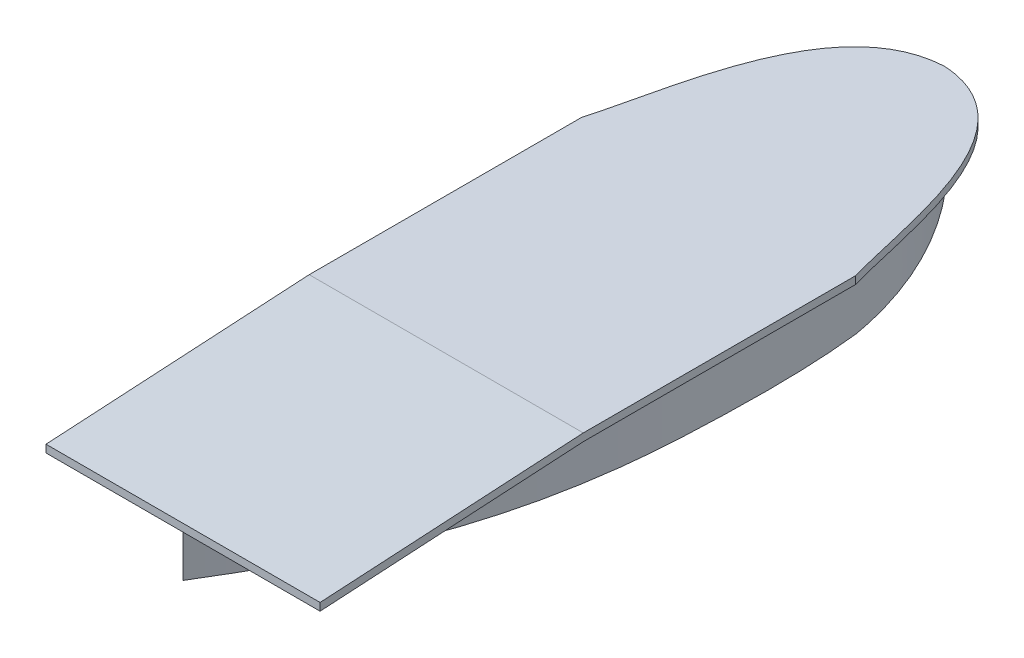
SolidWorks part; units mm, degrees
ref_plane "Front Plane" through (0, 0, 0) normal (0, 0, 1) x (1, 0, 0)
ref_plane "Top Plane" through (0, 0, 0) normal (0, 1, 0) x (1, 0, 0)
ref_plane "Right Plane" through (0, 0, 0) normal (1, 0, 0) x (0, 0, -1)
sketch "Sketch1" plane through (0, 0, 0) normal (0, 1, 0) x (1, 0, 0)
  line L0 (457.2, 5000) -> (457.2, 0) construction
  line L1 (0, 0) -> (914.4, 0) construction
  line L2 (0, 0) -> (0, 5000) construction
  line L3 (0, 5000) -> (914.4, 5000) construction
  line L4 (914.4, 0) -> (914.4, 5000) construction
  spline S0 degree 3 poles (457.2, 5000) (728.9155, 4811.3495) (923.1397, 4099.3682) (934.5582, 2393.6679) (728.4213, 982.7468) (457.2, 0) knots 0 0 0 0 0.183022 0.404936 1 1 1 1
  spline S1 degree 3 poles (457.2, 5000) (185.4845, 4811.3495) (-8.7397, 4099.3682) (-20.1582, 2393.6679) (185.9787, 982.7468) (457.2, 0) knots 0 0 0 0 0.183022 0.404936 1 1 1 1
  point P7 (180.2619, 4246.948)
  point P8 (228.0901, 3101.4628)
  point P9 (257.8987, 1620.2434)
  point P11 (0, 0)
  point P19 (104.7875, 4248.6526)
  point P20 (0, 3028.8666)
  point P21 (130.306, 1569.2064)
  point P22 (48.6467, 4172.097)
  point P23 (252.795, 4789.6455)
  dimension "D1" = 5000
  dimension "D2" = 914.4
extrude "Boss-Extrude1" add sketch "Sketch1" along normal blind 750 contours S0 S1
sketch "Sketch2" plane through (0, 0, 0) normal (1, 0, 0) x (0, 0, -1)
  line L10 (5000, 750) -> (0, 750) construction
  line L15 (1728.3497, 750) -> (0, 650)
  line L16 (0, 750) -> (0, 0) construction
  line L17 (1728.3497, 750) -> (3617.238, 750)
  line L18 (0, 0) -> (5000, 0) construction
  line L19 (0, 375) -> (1805.008, 0)
  line L20 (1805.008, 0) -> (3989.7721, 0)
  line L21 (0, 650) -> (0, 375)
  line L22 (5000, 750) -> (5000, 0) construction
  line L23 (-768.5235, 1443.0864) -> (6207.3897, 1443.0864)
  line L24 (-768.5235, 1443.0864) -> (-768.5235, -1130.4451)
  line L25 (-768.5235, -1130.4451) -> (6207.3897, -1130.4451)
  line L26 (6207.3897, 1443.0864) -> (6207.3897, -1130.4451)
  line L27 (3617.238, 750) -> (5000, 750)
  line L28 (5000, 750) -> (5000, 375)
  spline S1 degree 2 poles (5000, 375) (4563.55, 43.5842) (3989.7721, 0) knots 0 0 0 1 1 1
  dimension "D1" = 100
extrude "Cut-Extrude1" cut sketch "Sketch2" along normal blind 2867
sketch "Sketch3" plane through (0, 0, 0) normal (1, 0, 0) x (0, 0, -1)
  line L12 (3617.238, 800) -> (1728.3497, 800)
  line L13 (1728.3497, 800) -> (0, 700)
  line L14 (1728.3497, 750) -> (0, 650) construction
  line L15 (3617.238, 750) -> (1728.3497, 750) construction
  line L16 (1728.3497, 750) -> (0, 650)
  line L17 (3617.238, 750) -> (1728.3497, 750)
  line L18 (0, 700) -> (0, 650)
  line L20 (3617.238, 800) -> (5569.1616, 800)
  line L21 (5569.1616, 800) -> (5569.1616, 750)
  line L22 (5569.1616, 750) -> (3617.238, 750)
  parabola Q3 (3617.238, 750) -> (5000, 375) focus (4040.6415, -886.3716) apex (4554.2714, 572.4153) construction
  parabola Q4 (3617.238, 750) -> (5000, 375) focus (4040.6415, -886.3716) apex (4554.2714, 572.4153)
extrude "Boss-Extrude2" add sketch "Sketch3" along normal blind 2921 and the other way blind 1210 contours L17 L16 L18 L13 L12 L20 L21 L22
sketch "Sketch5" plane through (0, 0, 0) normal (0, 1, 0) x (1, 0, 0)
  line L0 (457.2, 0) -> (2921, 0) construction
  line L1 (1357.2, 0) -> (-442.8, 0)
  line L2 (1357.2, 0) -> (1357.2, 3516.9727)
  line L4 (-442.8, 0) -> (-442.8, 3516.9727)
  line L6 (457.2, 5000) -> (457.2, 0) construction
  line L8 (4229.4532, 6147.4401) -> (-2468.9674, 6147.4401)
  line L9 (4229.4532, 6147.4401) -> (4229.4532, -176.8945)
  line L10 (4229.4532, -176.8945) -> (-2468.9674, -176.8945)
  line L11 (-2468.9674, 6147.4401) -> (-2468.9674, -176.8945)
  spline S2 degree 3 poles (457.2, 5000) (1122.8861, 4963.2034) (1222.4204, 3985.8742) (1357.2, 3516.9727) knots 0 0 0 0 1 1 1 1
  spline S3 degree 3 poles (457.2, 5000) (-208.4861, 4963.2034) (-308.0204, 3985.8742) (-442.8, 3516.9727) knots 0 0 0 0 1 1 1 1
  point P8 (457.2, 0)
extrude "Cut-Extrude3" cut sketch "Sketch5" along normal blind 3100 contours L8 L11 L10 L9
fillet "Fillet2" radius 10000 1 edges at (457.2, 0, -1805.008)
